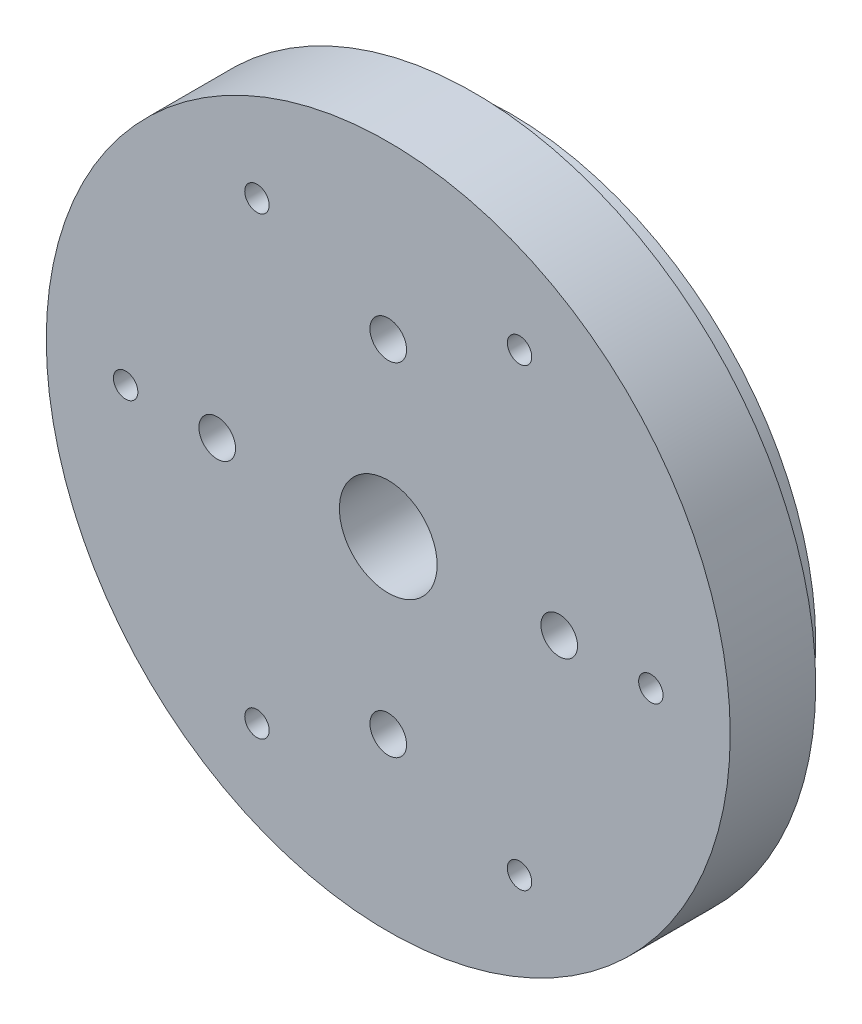
SolidWorks part; units mm, degrees
material "ABS"
ref_plane "Front Plane" through (0, 0, 0) normal (0, 0, 1) x (1, 0, 0)
ref_plane "Top Plane" through (0, 0, 0) normal (0, 1, 0) x (1, 0, 0)
ref_plane "Right Plane" through (0, 0, 0) normal (1, 0, 0) x (0, 0, -1)
sketch "Sketch1" plane through (0, 0, 0) normal (0, 0, 1) x (1, 0, 0)
  line L0 (0, 34.8882) -> (0, -35.3531) construction
  line L1 (0, -35.3531) -> (0, 0) construction
  line L2 (0, 0) -> (-48.3544, 0) construction
  line L3 (-48.3544, 0) -> (47.9766, 0) construction
  circle A0 centre (0, 0) radius 28
  circle A1 centre (0, 0) radius 4
  circle A2 centre (0, 0) radius 14 construction
  circle A3 centre (0, 14) radius 1.5
  circle A4 centre (14, 0) radius 1.5
  circle A5 centre (0, -14) radius 1.5
  circle A6 centre (-14, 0) radius 1.5
  dimension "D1" = 28
extrude "Boss-Extrude1" add sketch "Sketch1" along normal blind 7
sketch "Sketch2" plane through (0, 0, 0) normal (0, 0, -1) x (-1, 0, 0)
  circle A0 centre (0, 0) radius 18
  circle A1 centre (0, 0) radius 25
extrude "Boss-Extrude2" add sketch "Sketch2" along normal blind 3
sketch "Sketch3" plane through (0, 0, -3) normal (0, 0, -1) x (-1, 0, 0)
  line L0 (-56.257, 0) -> (43.8734, 0) construction
  line L1 (18.9939, 32.8984) -> (0, 0) construction
  line L2 (0, 0) -> (-22.2857, -38.5999) construction
  line L3 (-22.7924, 39.4776) -> (0, 0) construction
  line L4 (0, 0) -> (23.8769, -41.356) construction
  circle A0 centre (0, 0) radius 21.5 construction
  circle A1 centre (-10.75, 18.6195) radius 1
  circle A2 centre (10.75, 18.6195) radius 1
  circle A3 centre (21.5, 0) radius 1
  circle A4 centre (10.75, -18.6195) radius 1
  circle A5 centre (-10.75, -18.6195) radius 1
  circle A6 centre (-21.5, 0) radius 1
  dimension "D3" = 2
  dimension "D1" = 60
  dimension "D2" = 60
extrude "Cut-Extrude1" cut sketch "Sketch3" against normal blind 10
